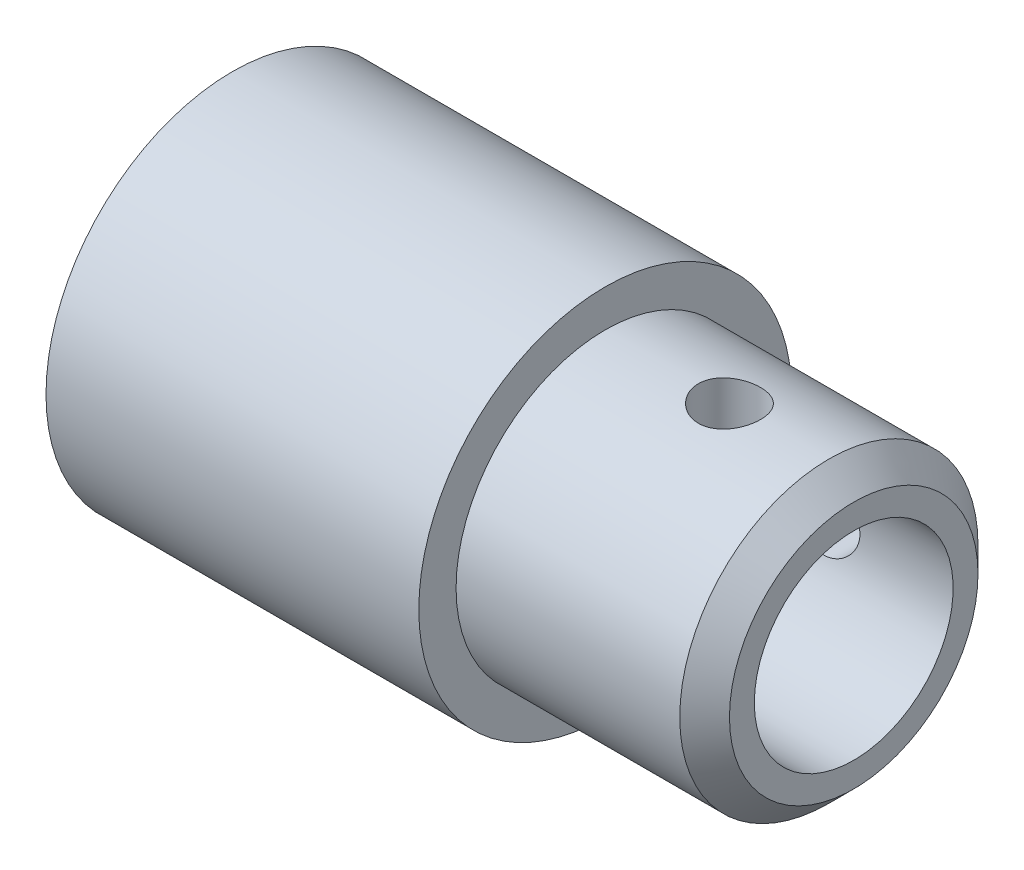
SolidWorks part; units mm, degrees
ref_plane "Front Plane" through (0, 0, 0) normal (0, 0, 1) x (1, 0, 0)
ref_plane "Top Plane" through (0, 0, 0) normal (0, 1, 0) x (1, 0, 0)
ref_plane "Right Plane" through (0, 0, 0) normal (1, 0, 0) x (0, 0, -1)
sketch "Sketch1" plane through (0, 0, 0) normal (0, 0, 1) x (1, 0, 0)
  line L0 (0, 0) -> (25, 0) construction
  line L1 (0, 4) -> (0, 6)
  line L4 (0, 6) -> (25, 6)
  line L5 (25, 6) -> (25, 4)
  line L6 (25, 4) -> (0, 4)
  dimension "D_s" = 8
  dimension "D1." = 12
  dimension "L" = 25
revolve "Revolve1" add sketch "Sketch1" angle 360 about L0
sketch "Sketch2" plane through (0, 0, 0) normal (0, 0, 1) x (1, 0, 0)
  line L1 (0, 4) -> (15, 4)
  line L2 (0, 4) -> (0, 7.5)
  line L3 (0, 7.5) -> (15, 7.5)
  line L4 (15, 4) -> (15, 7.5)
  line L5 (0, 0) -> (25, 0) construction
  line L6 (25, 4) -> (0, 4) construction
  dimension "W" = 15
  dimension "D2." = 15
revolve "Revolve2" add sketch "Sketch2" angle 360 about L5
ref_plane "Plane1" through (0, 6, 0) normal (0, 1, 0) x (1, 0, 0)
hole_wizard "Tapped Hole1" positions "Sketch4" profile "Sketch3" tap size "M3x0.5" standard "JIS"
sketch "Sketch4" plane through (0, 6, 0) normal (0, 1, 0) x (1, 0, 0)
  line L0 (0, 0) -> (20, 0) construction
  line L2 (25, -6) -> (25, 6) construction
  point P0 (20, 0)
  dimension "L_s" = 5
sketch "Sketch3" plane through (20, 6, 0) normal (1, 0, 0) x (0, 0, 1)
  line L0 (0, 0) -> (0, 2)
  line L1 (0, 2) -> (1.25, 2)
  line L2 (1.25, 2) -> (1.25, 0)
  line L5 (1.25, 0) -> (0, 0)
  line L11 (0, 0) -> (0, 2) construction
  dimension "Thru Tap Drill Dia." = 2.5
  dimension "Thru Tap Drill Depth" = 2
cosmetic thread "Hole Thread1" parameters "M"=3
pattern_circular "CirPattern1" count 2 over 90 about axis through (0, 0, 0) along (-1, 0, 0) of "Tapped Hole1"
chamfer "Chamfer1" distance 1 angle 45 1 edges at (25, 0, 6)
equation "\"Plain dim\"= \"D1.@Sketch1\" * 0.5"
